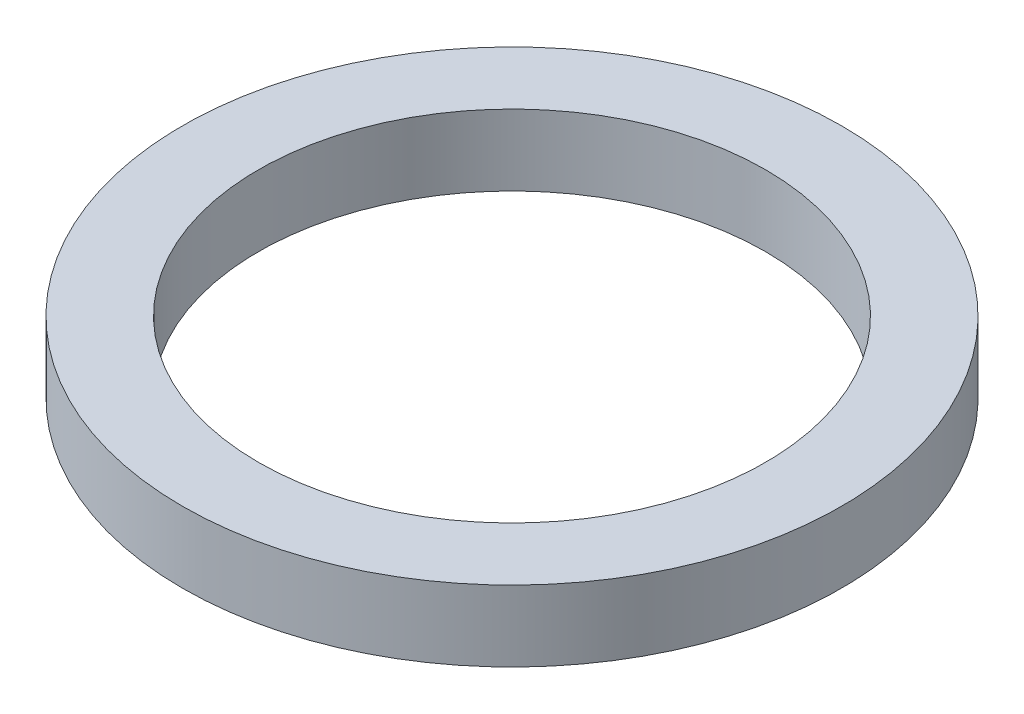
SolidWorks part; units mm, degrees
ref_plane "Front" through (0, 0, 0) normal (0, 0, 1) x (1, 0, 0)
ref_plane "Top" through (0, 0, 0) normal (0, 1, 0) x (1, 0, 0)
ref_plane "Right" through (0, 0, 0) normal (1, 0, 0) x (0, 0, -1)
sketch "Sketch1" plane through (0, 0, 0) normal (0, 1, 0) x (1, 0, 0)
  circle A0 centre (0, 0) radius 25
  circle A1 centre (0, 0) radius 32.5
  dimension "D1" = 50
  dimension "D2" = 65
extrude "Boss-Extrude1" add sketch "Sketch1" along normal blind 7
